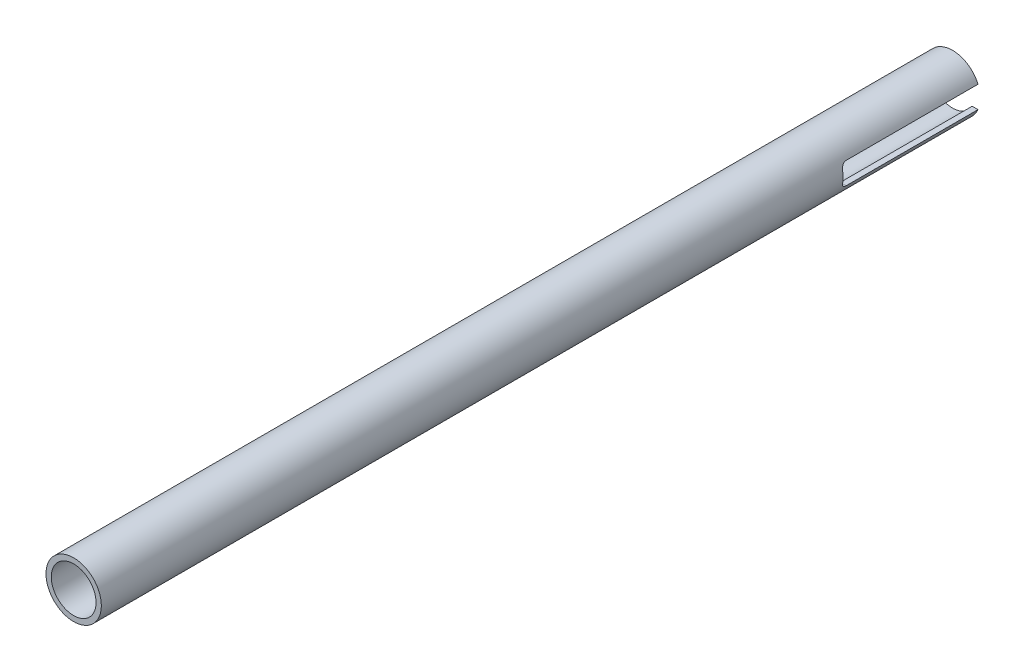
SolidWorks part; units mm, degrees
material "AISI 4130 Steel, annealed at 865C"
ref_plane "Front Plane" through (0, 0, 0) normal (0, 0, 1) x (1, 0, 0)
ref_plane "Top Plane" through (0, 0, 0) normal (0, 1, 0) x (1, 0, 0)
ref_plane "Right Plane" through (0, 0, 0) normal (1, 0, 0) x (0, 0, -1)
sketch "Sketch1" plane through (0, 0, 0) normal (0, 0, 1) x (1, 0, 0)
  circle A0 centre (0, 0) radius 6.477
  circle A1 centre (0, 0) radius 8.001
  dimension "D1" = 12.954
  dimension "D2" = 16.002
extrude "Boss-Extrude1" add sketch "Sketch1" along normal blind 254
sketch "Sketch2" plane through (0, 0, 0) normal (1, 0, 0) x (0, 0, -1)
  line L0 (0, 3.175) -> (-38.1, 3.175)
  line L1 (0, 55) -> (0, -55) construction
  line L2 (-38.1, -3.175) -> (0, -3.175)
  line L3 (-39.624, 1.651) -> (-39.624, -1.651)
  line L4 (0, -8.001) -> (0, 8.001) construction
  arc A0 (-39.624, 1.651) -> (-38.1, 3.175) centre (-38.1, 1.651) cw
  arc A1 (-38.1, -3.175) -> (-39.624, -1.651) centre (-38.1, -1.651) cw
  dimension "D5" = 38.1
  dimension "D6" = 39.624
  dimension "D1" = 39.624
  dimension "D2" = 38.1
  dimension "D3" = 6.35
  dimension "D4" = 3.175
extrude "Cut-Extrude2" cut sketch "Sketch2" against normal through all both and the other way through all
